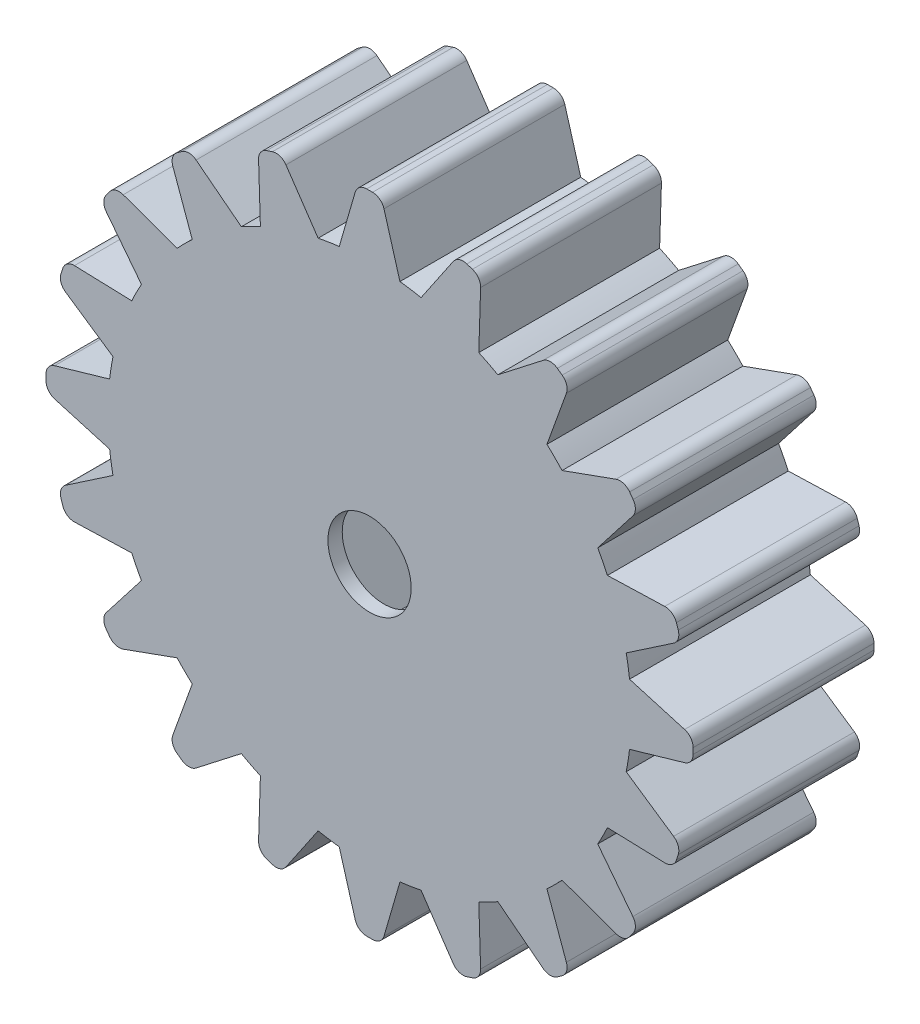
SolidWorks part; units mm, degrees
ref_plane "Front Plane" through (0, 0, 0) normal (0, 0, 1) x (1, 0, 0)
ref_plane "Top Plane" through (0, 0, 0) normal (0, 1, 0) x (1, 0, 0)
ref_plane "Right Plane" through (0, 0, 0) normal (1, 0, 0) x (0, 0, -1)
sketch "Sketch1" plane through (0, 0, 0) normal (0, 0, 1) x (1, 0, 0)
  line L0 (0, 0) -> (0, 6.9703) construction
  line L1 (-0.1245, 13.6) -> (0.1245, 13.6)
  line L2 (-0.6047, 13.2393) -> (-1.276, 10.9257)
  line L3 (0.6047, 13.2393) -> (1.276, 10.9257)
  line L4 (3.5161, 12.7782) -> (2.1627, 10.7853)
  line L5 (4.0843, 12.9728) -> (4.321, 12.8959)
  line L6 (4.6662, 12.4045) -> (4.5898, 9.9967)
  line L7 (7.2927, 11.0663) -> (5.3897, 9.5891)
  line L8 (7.8932, 11.0758) -> (8.0946, 10.9295)
  line L9 (8.2711, 10.3554) -> (7.4543, 8.0891)
  line L10 (10.3554, 8.2711) -> (8.0891, 7.4543)
  line L11 (10.9295, 8.0946) -> (11.0758, 7.8932)
  line L12 (11.0663, 7.2927) -> (9.5891, 5.3897)
  line L13 (12.4045, 4.6662) -> (9.9967, 4.5898)
  line L14 (12.8959, 4.321) -> (12.9728, 4.0843)
  line L15 (12.7782, 3.5161) -> (10.7853, 2.1627)
  line L16 (13.2393, 0.6047) -> (10.9257, 1.276)
  line L17 (13.6, 0.1245) -> (13.6, -0.1245)
  line L18 (13.2393, -0.6047) -> (10.9257, -1.276)
  line L19 (12.7782, -3.5161) -> (10.7853, -2.1627)
  line L20 (12.9728, -4.0843) -> (12.8959, -4.321)
  line L21 (12.4045, -4.6662) -> (9.9967, -4.5898)
  line L22 (11.0663, -7.2927) -> (9.5891, -5.3897)
  line L23 (11.0758, -7.8932) -> (10.9295, -8.0946)
  line L24 (10.3554, -8.2711) -> (8.0891, -7.4543)
  line L25 (8.2711, -10.3554) -> (7.4543, -8.0891)
  line L26 (8.0946, -10.9295) -> (7.8932, -11.0758)
  line L27 (7.2927, -11.0663) -> (5.3897, -9.5891)
  line L28 (4.6662, -12.4045) -> (4.5898, -9.9967)
  line L29 (4.321, -12.8959) -> (4.0843, -12.9728)
  line L30 (3.5161, -12.7782) -> (2.1627, -10.7853)
  line L31 (0.6047, -13.2393) -> (1.276, -10.9257)
  line L32 (0.1245, -13.6) -> (-0.1245, -13.6)
  line L33 (-0.6047, -13.2393) -> (-1.276, -10.9257)
  line L34 (-3.5161, -12.7782) -> (-2.1627, -10.7853)
  line L35 (-4.0843, -12.9728) -> (-4.321, -12.8959)
  line L36 (-4.6662, -12.4045) -> (-4.5898, -9.9967)
  line L37 (-7.2927, -11.0663) -> (-5.3897, -9.5891)
  line L38 (-7.8932, -11.0758) -> (-8.0946, -10.9295)
  line L39 (-8.2711, -10.3554) -> (-7.4543, -8.0891)
  line L40 (-10.3554, -8.2711) -> (-8.0891, -7.4543)
  line L41 (-10.9295, -8.0946) -> (-11.0758, -7.8932)
  line L42 (-11.0663, -7.2927) -> (-9.5891, -5.3897)
  line L43 (-12.4045, -4.6662) -> (-9.9967, -4.5898)
  line L44 (-12.8959, -4.321) -> (-12.9728, -4.0843)
  line L45 (-12.7782, -3.5161) -> (-10.7853, -2.1627)
  line L46 (-13.2393, -0.6047) -> (-10.9257, -1.276)
  line L47 (-13.6, -0.1245) -> (-13.6, 0.1245)
  line L48 (-13.2393, 0.6047) -> (-10.9257, 1.276)
  line L49 (-12.7782, 3.5161) -> (-10.7853, 2.1627)
  line L50 (-12.9728, 4.0843) -> (-12.8959, 4.321)
  line L51 (-12.4045, 4.6662) -> (-9.9967, 4.5898)
  line L52 (-11.0663, 7.2927) -> (-9.5891, 5.3897)
  line L53 (-11.0758, 7.8932) -> (-10.9295, 8.0946)
  line L54 (-10.3554, 8.2711) -> (-8.0891, 7.4543)
  line L55 (-8.2711, 10.3554) -> (-7.4543, 8.0891)
  line L56 (-8.0946, 10.9295) -> (-7.8932, 11.0758)
  line L57 (-7.2927, 11.0663) -> (-5.3897, 9.5891)
  line L58 (-4.6662, 12.4045) -> (-4.5898, 9.9967)
  line L59 (-4.321, 12.8959) -> (-4.0843, 12.9728)
  line L60 (-3.5161, 12.7782) -> (-2.1627, 10.7853)
  arc A0 (2.1627, 10.7853) -> (1.276, 10.9257) centre (0, 0) ccw
  arc A1 (0.1245, 13.6) -> (0.6047, 13.2393) centre (0.1245, 13.1) cw
  arc A2 (-0.1245, 13.6) -> (-0.6047, 13.2393) centre (-0.1245, 13.1) ccw
  arc A3 (4.0843, 12.9728) -> (3.5161, 12.7782) centre (3.9298, 12.4973) ccw
  arc A4 (4.321, 12.8959) -> (4.6662, 12.4045) centre (4.1665, 12.4204) cw
  arc A5 (7.8932, 11.0758) -> (7.2927, 11.0663) centre (7.5993, 10.6713) ccw
  arc A6 (8.0946, 10.9295) -> (8.2711, 10.3554) centre (7.8007, 10.525) cw
  arc A7 (10.9295, 8.0946) -> (10.3554, 8.2711) centre (10.525, 7.8007) ccw
  arc A8 (11.0758, 7.8932) -> (11.0663, 7.2927) centre (10.6713, 7.5993) cw
  arc A9 (12.8959, 4.321) -> (12.4045, 4.6662) centre (12.4204, 4.1665) ccw
  arc A10 (12.9728, 4.0843) -> (12.7782, 3.5161) centre (12.4973, 3.9298) cw
  arc A11 (13.6, 0.1245) -> (13.2393, 0.6047) centre (13.1, 0.1245) ccw
  arc A12 (13.6, -0.1245) -> (13.2393, -0.6047) centre (13.1, -0.1245) cw
  arc A13 (12.9728, -4.0843) -> (12.7782, -3.5161) centre (12.4973, -3.9298) ccw
  arc A14 (12.8959, -4.321) -> (12.4045, -4.6662) centre (12.4204, -4.1665) cw
  arc A15 (11.0758, -7.8932) -> (11.0663, -7.2927) centre (10.6713, -7.5993) ccw
  arc A16 (10.9295, -8.0946) -> (10.3554, -8.2711) centre (10.525, -7.8007) cw
  arc A17 (8.0946, -10.9295) -> (8.2711, -10.3554) centre (7.8007, -10.525) ccw
  arc A18 (7.8932, -11.0758) -> (7.2927, -11.0663) centre (7.5993, -10.6713) cw
  arc A19 (4.321, -12.8959) -> (4.6662, -12.4045) centre (4.1665, -12.4204) ccw
  arc A20 (4.0843, -12.9728) -> (3.5161, -12.7782) centre (3.9298, -12.4973) cw
  arc A21 (0.1245, -13.6) -> (0.6047, -13.2393) centre (0.1245, -13.1) ccw
  arc A22 (-0.1245, -13.6) -> (-0.6047, -13.2393) centre (-0.1245, -13.1) cw
  arc A23 (-4.0843, -12.9728) -> (-3.5161, -12.7782) centre (-3.9298, -12.4973) ccw
  arc A24 (-4.321, -12.8959) -> (-4.6662, -12.4045) centre (-4.1665, -12.4204) cw
  arc A25 (-7.8932, -11.0758) -> (-7.2927, -11.0663) centre (-7.5993, -10.6713) ccw
  arc A26 (-8.0946, -10.9295) -> (-8.2711, -10.3554) centre (-7.8007, -10.525) cw
  arc A27 (-10.9295, -8.0946) -> (-10.3554, -8.2711) centre (-10.525, -7.8007) ccw
  arc A28 (-11.0758, -7.8932) -> (-11.0663, -7.2927) centre (-10.6713, -7.5993) cw
  arc A29 (-12.8959, -4.321) -> (-12.4045, -4.6662) centre (-12.4204, -4.1665) ccw
  arc A30 (-12.9728, -4.0843) -> (-12.7782, -3.5161) centre (-12.4973, -3.9298) cw
  arc A31 (-13.6, -0.1245) -> (-13.2393, -0.6047) centre (-13.1, -0.1245) ccw
  arc A32 (-13.6, 0.1245) -> (-13.2393, 0.6047) centre (-13.1, 0.1245) cw
  arc A33 (-12.9728, 4.0843) -> (-12.7782, 3.5161) centre (-12.4973, 3.9298) ccw
  arc A34 (-12.8959, 4.321) -> (-12.4045, 4.6662) centre (-12.4204, 4.1665) cw
  arc A35 (-11.0758, 7.8932) -> (-11.0663, 7.2927) centre (-10.6713, 7.5993) ccw
  arc A36 (-10.9295, 8.0946) -> (-10.3554, 8.2711) centre (-10.525, 7.8007) cw
  arc A37 (-8.0946, 10.9295) -> (-8.2711, 10.3554) centre (-7.8007, 10.525) ccw
  arc A38 (-7.8932, 11.0758) -> (-7.2927, 11.0663) centre (-7.5993, 10.6713) cw
  arc A39 (-4.321, 12.8959) -> (-4.6662, 12.4045) centre (-4.1665, 12.4204) ccw
  arc A40 (-4.0843, 12.9728) -> (-3.5161, 12.7782) centre (-3.9298, 12.4973) cw
  arc A41 (-1.276, 10.9257) -> (-2.1627, 10.7853) centre (0, 0) ccw
  arc A42 (-4.5898, 9.9967) -> (-5.3897, 9.5891) centre (0, 0) ccw
  arc A43 (-7.4543, 8.0891) -> (-8.0891, 7.4543) centre (0, 0) ccw
  arc A44 (-9.5891, 5.3897) -> (-9.9967, 4.5898) centre (0, 0) ccw
  arc A45 (-10.7853, 2.1627) -> (-10.9257, 1.276) centre (0, 0) ccw
  arc A46 (-10.9257, -1.276) -> (-10.7853, -2.1627) centre (0, 0) ccw
  arc A47 (-9.9967, -4.5898) -> (-9.5891, -5.3897) centre (0, 0) ccw
  arc A48 (-8.0891, -7.4543) -> (-7.4543, -8.0891) centre (0, 0) ccw
  arc A49 (-5.3897, -9.5891) -> (-4.5898, -9.9967) centre (0, 0) ccw
  arc A50 (-2.1627, -10.7853) -> (-1.276, -10.9257) centre (0, 0) ccw
  arc A51 (1.276, -10.9257) -> (2.1627, -10.7853) centre (0, 0) ccw
  arc A52 (4.5898, -9.9967) -> (5.3897, -9.5891) centre (0, 0) ccw
  arc A53 (7.4543, -8.0891) -> (8.0891, -7.4543) centre (0, 0) ccw
  arc A54 (9.5891, -5.3897) -> (9.9967, -4.5898) centre (0, 0) ccw
  arc A55 (10.7853, -2.1627) -> (10.9257, -1.276) centre (0, 0) ccw
  arc A56 (10.9257, 1.276) -> (10.7853, 2.1627) centre (0, 0) ccw
  arc A57 (9.9967, 4.5898) -> (9.5891, 5.3897) centre (0, 0) ccw
  arc A58 (8.0891, 7.4543) -> (7.4543, 8.0891) centre (0, 0) ccw
  arc A59 (5.3897, 9.5891) -> (4.5898, 9.9967) centre (0, 0) ccw
  point P7 (0, 13.6)
  point P12 (0.5, 13.6)
  point P15 (-0.5, 13.6)
  point P170 (0, 0)
  dimension "D1" = 22
  dimension "D4" = 0.5
  dimension "D2" = 13.6
  dimension "D3" = 1
  dimension "D5" = 20
extrude "Boss-Extrude1" add sketch "Sketch1" along normal blind 7.6
sketch "Sketch4" plane through (0, 0, 0) normal (0, 0, -1) x (-1, 0, 0)
  line L0 (-6.9264, -0.1594) -> (-3.3251, -6.0781) construction
  line L1 (-3.3251, -6.0781) -> (3.6013, -5.9187) construction
  line L2 (3.6013, -5.9187) -> (6.9264, 0.1594) construction
  line L3 (6.9264, 0.1594) -> (3.3251, 6.0781) construction
  line L4 (3.3251, 6.0781) -> (-3.6013, 5.9187) construction
  line L5 (-3.6013, 5.9187) -> (-6.9264, -0.1594) construction
  line L6 (-6.9264, -0.1594) -> (-3.3251, -6.0781)
  line L7 (-3.3251, -6.0781) -> (3.6013, -5.9187)
  line L8 (3.6013, -5.9187) -> (6.9264, 0.1594)
  line L9 (6.9264, 0.1594) -> (3.3251, 6.0781)
  line L10 (3.3251, 6.0781) -> (-3.6013, 5.9187)
  line L11 (-3.6013, 5.9187) -> (-6.9264, -0.1594)
  circle A0 centre (0, 0) radius 1.75
  dimension "D1" = 3.5
extrude "Cut-Extrude1" cut sketch "Sketch4" against normal blind 7
sketch "Sketch5" plane through (0, 0, 0) normal (0, 0, -1) x (-1, 0, 0)
  circle A0 centre (0, 0) radius 1.75
  dimension "D1" = 3.5
extrude "Cut-Extrude2" cut sketch "Sketch5" against normal through all
